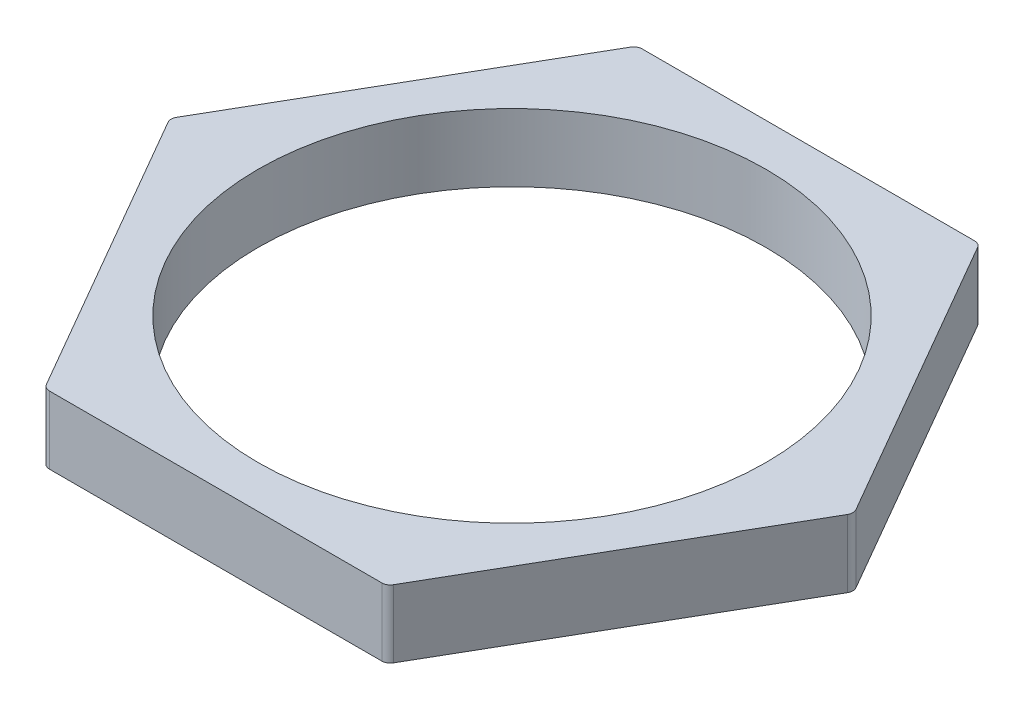
SolidWorks part; units mm, degrees
material "PET"
ref_plane "Alzado" through (0, 0, 0) normal (0, 0, 1) x (1, 0, 0)
ref_plane "Planta" through (0, 0, 0) normal (0, 1, 0) x (1, 0, 0)
ref_plane "Vista lateral" through (0, 0, 0) normal (1, 0, 0) x (0, 0, -1)
ref_plane "Plano1" through (0, 4, 0) normal (0, 1, 0) x (1, 0, 0)
sketch "Croquis1" plane through (0, 4, 0) normal (0, 1, 0) x (1, 0, 0)
  line L0 (9.815, 17.5) -> (-9.815, 17.5)
  line L1 (-10.248, 17.25) -> (-20.0629, 0.25)
  line L2 (-20.0629, -0.25) -> (-10.248, -17.25)
  line L3 (-9.815, -17.5) -> (9.815, -17.5)
  line L4 (10.248, -17.25) -> (20.0629, -0.25)
  line L5 (20.0629, 0.25) -> (10.248, 17.25)
  circle A0 centre (0, 0) radius 15
  arc A1 (-9.815, 17.5) -> (-10.248, 17.25) centre (-9.815, 17) ccw
  arc A2 (-20.0629, 0.25) -> (-20.0629, -0.25) centre (-19.6299, 0) ccw
  arc A3 (-10.248, -17.25) -> (-9.815, -17.5) centre (-9.815, -17) ccw
  arc A4 (9.815, -17.5) -> (10.248, -17.25) centre (9.815, -17) ccw
  arc A5 (20.0629, -0.25) -> (20.0629, 0.25) centre (19.6299, 0) ccw
  arc A6 (10.248, 17.25) -> (9.815, 17.5) centre (9.815, 17) ccw
extrude "Saliente-Extruir1" add sketch "Croquis1" against normal blind 4
